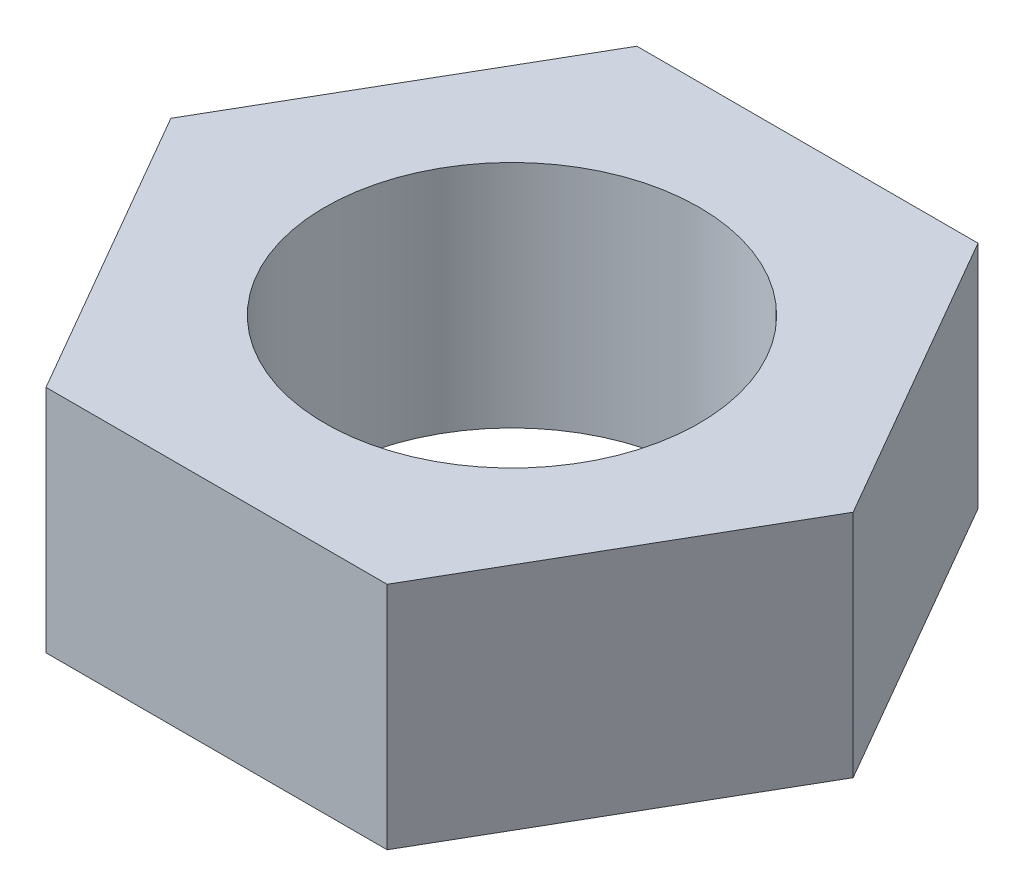
SolidWorks part; units mm, degrees
ref_plane "Front Plane" through (0, 0, 0) normal (0, 0, 1) x (1, 0, 0)
ref_plane "Top Plane" through (0, 0, 0) normal (0, 1, 0) x (1, 0, 0)
ref_plane "Right Plane" through (0, 0, 0) normal (1, 0, 0) x (0, 0, -1)
sketch "Sketch1" plane through (0, 0, 0) normal (0, 1, 0) x (1, 0, 0)
  line L1 (3.1899, -5.525) -> (6.3797, 0)
  line L2 (6.3797, 0) -> (3.1899, 5.525)
  line L3 (3.1899, 5.525) -> (-3.1899, 5.525)
  line L4 (-3.1899, 5.525) -> (-6.3797, 0)
  line L5 (-6.3797, 0) -> (-3.1899, -5.525)
  line L6 (-3.1899, -5.525) -> (3.1899, -5.525)
  circle A0 centre (0, 0) radius 5.525 construction
  circle A1 centre (0, 0) radius 3.5
  dimension "D2" = 7
  dimension "D1" = 11.05
extrude "Boss-Extrude1" add sketch "Sketch1" along normal blind 4.3
